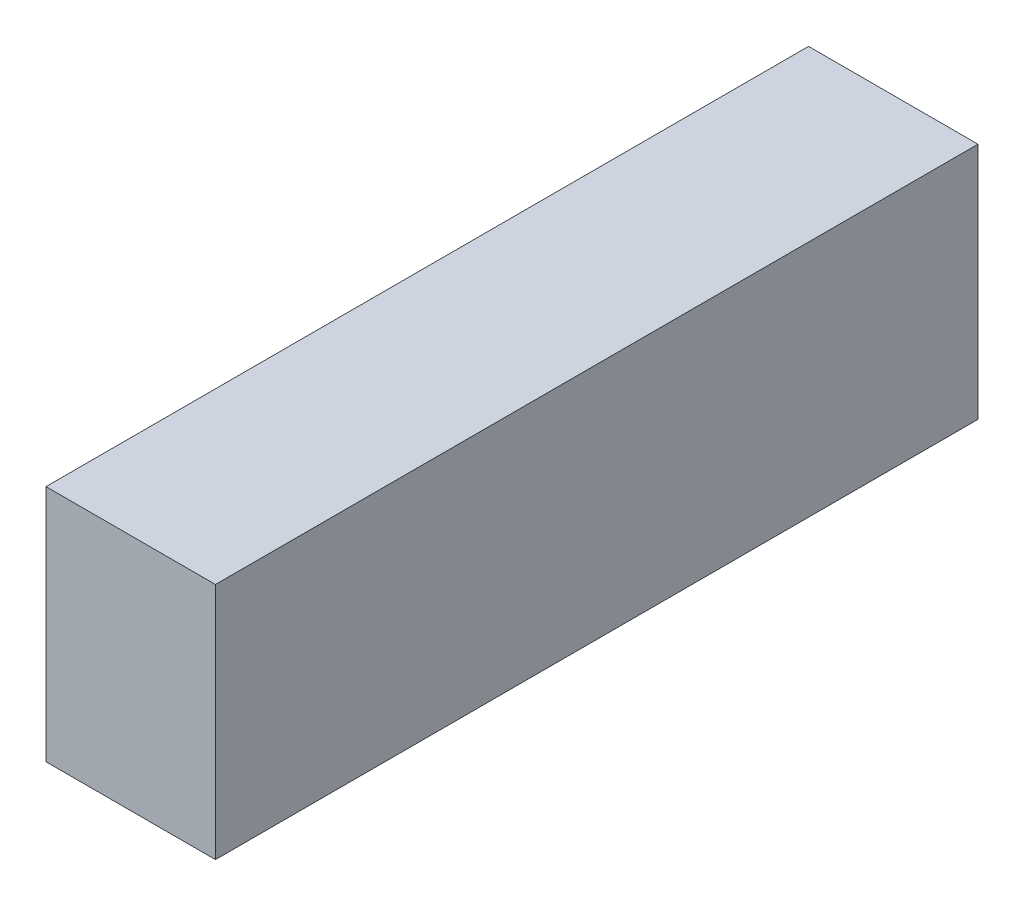
SolidWorks part; units mm, degrees
ref_plane "Front Plane" through (0, 0, 0) normal (0, 0, 1) x (1, 0, 0)
ref_plane "Top Plane" through (0, 0, 0) normal (0, 1, 0) x (1, 0, 0)
ref_plane "Right Plane" through (0, 0, 0) normal (1, 0, 0) x (0, 0, -1)
sketch "Sketch1" plane through (0, 0, 0) normal (0, 1, 0) x (1, 0, 0)
  line L0 (0, 0) -> (101.6, 0)
  line L1 (0, 0) -> (-101.6, 0)
  line L2 (101.6, 0) -> (101.6, 914.4)
  line L3 (-101.6, 0) -> (-101.6, 914.4)
  line L4 (-101.6, 914.4) -> (101.6, 914.4)
extrude "Boss-Extrude1" add sketch "Sketch1" along normal blind 285.75 contours L4 L2 L0 L1 L3
